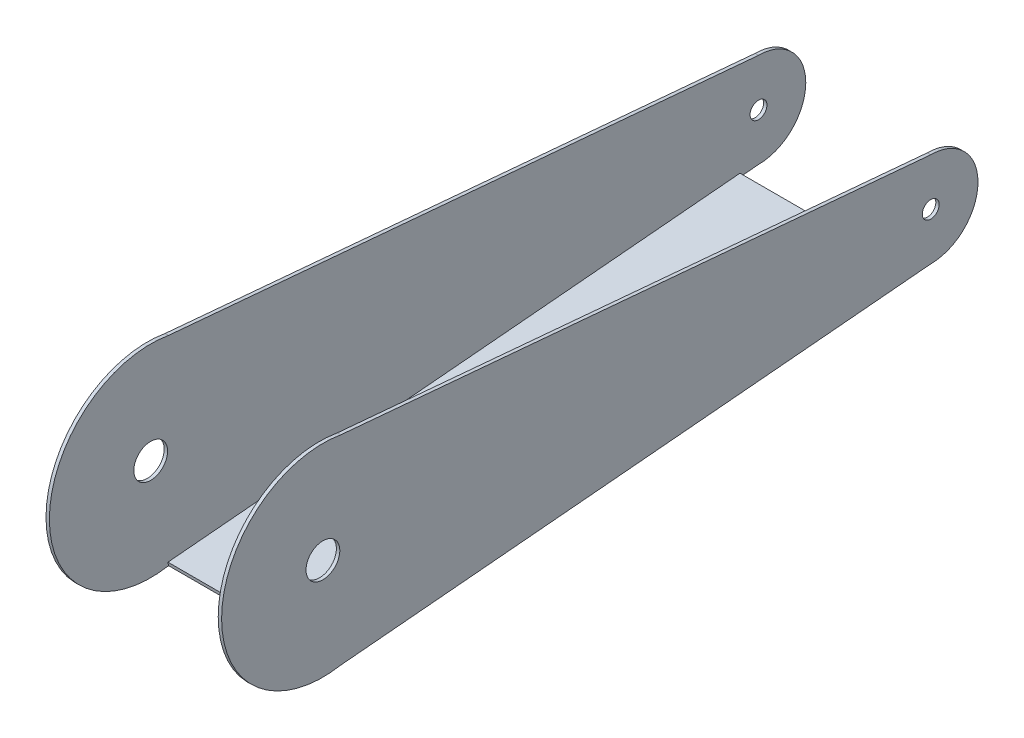
SolidWorks part; units mm, degrees
ref_plane "Front Plane" through (0, 0, 0) normal (0, 0, 1) x (1, 0, 0)
ref_plane "Top Plane" through (0, 0, 0) normal (0, 1, 0) x (1, 0, 0)
ref_plane "Right Plane" through (0, 0, 0) normal (1, 0, 0) x (0, 0, -1)
sketch "Sketch1" plane through (0, 0, 0) normal (1, 0, 0) x (0, 0, -1)
  line L0 (5.2915, 29.5296) -> (180, 14)
  line L2 (180, -14) -> (5.2915, -29.5296)
  arc A0 (5.2915, 29.5296) -> (5.2915, -29.5296) centre (0, 0) ccw
  arc A1 (180, -14) -> (180, 14) centre (180, 0) ccw
  circle A2 centre (0, 0) radius 5
  circle A3 centre (180, 0) radius 2.5
  dimension "D1" = 180
  dimension "D2" = 28
  dimension "D3" = 60
  dimension "D4" = 5
  dimension "D5" = 10
extrude "Boss-Extrude1" add sketch "Sketch1" along normal mid plane 52 contours L0 A1 L2 A0 | A2 | A3
sketch "Sketch2" plane through (0, 0, 0) normal (1, 0, 0) x (0, 0, -1)
  line L0 (5.2915, -29.5296) -> (5.1144, -28.5414)
  line L1 (180, -14) -> (174.5951, -14.4804)
  line L4 (174.5065, -13.4844) -> (5.1144, -28.5414)
  line L5 (5.2915, 29.5296) -> (180, 14) construction
  line L6 (5.2915, 29.5296) -> (180, 14)
  line L8 (180, -14) -> (5.2915, -29.5296) construction
  line L9 (174.5951, -14.4804) -> (174.5065, -13.4844)
  arc A8 (180, -14) -> (180, 14) centre (180, 0) ccw construction
  arc A9 (5.2915, 29.5296) -> (5.2915, -29.5296) centre (0, 0) ccw construction
  arc A10 (180, -14) -> (180, 14) centre (180, 0) ccw
  arc A11 (5.2915, 29.5296) -> (5.2915, -29.5296) centre (0, 0) ccw
extrude "Cut-Extrude1" cut sketch "Sketch2" against normal mid plane 50
